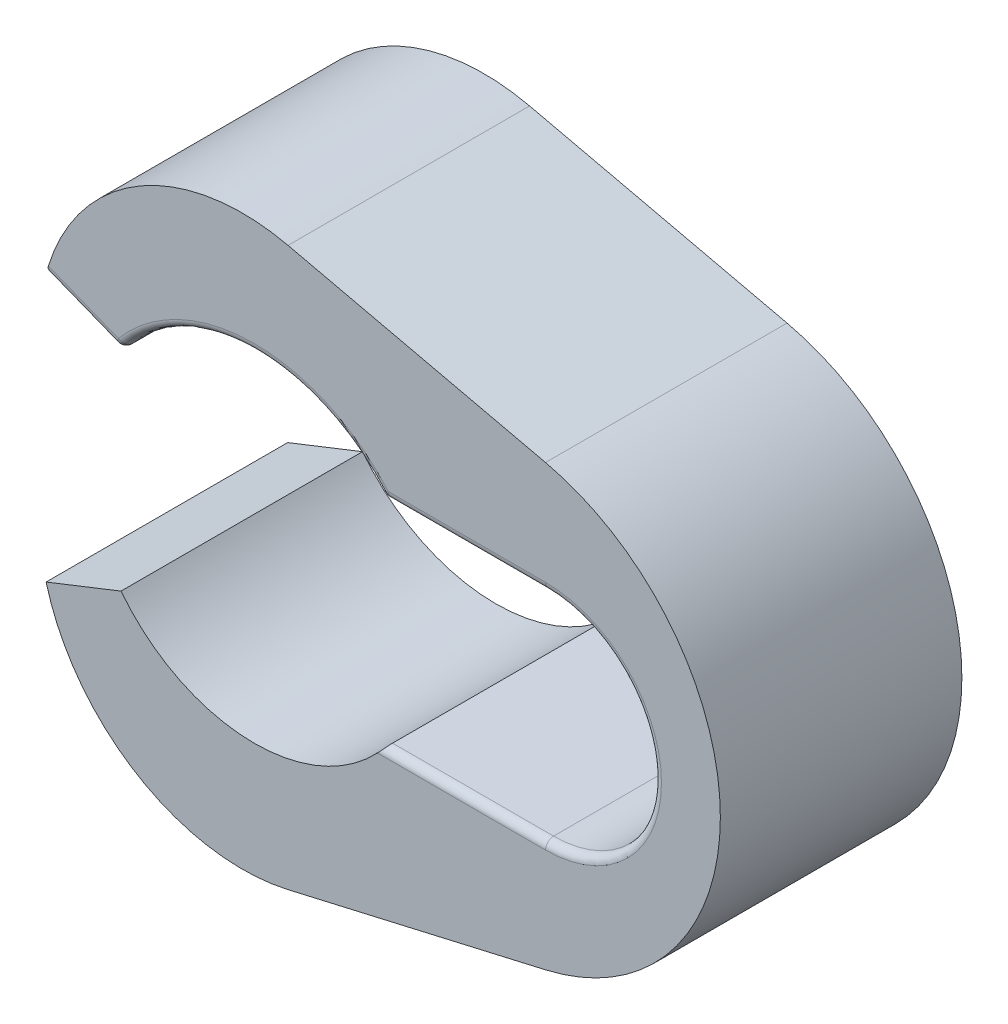
SolidWorks part; units mm, degrees
ref_plane "Plan de face" through (0, 0, 0) normal (0, 0, 1) x (1, 0, 0)
ref_plane "Plan de dessus" through (0, 0, 0) normal (0, 1, 0) x (1, 0, 0)
ref_plane "Plan de droite" through (0, 0, 0) normal (1, 0, 0) x (0, 0, -1)
sketch "Esquisse1" plane through (0, 0, 0) normal (0, 0, 1) x (1, 0, 0)
  line L0 (8.0846, 6.7) -> (18.0846, 6.7)
  line L2 (-8.2813, 6.4552) -> (-12.9318, 8.2919)
  line L3 (2.0932, 17.3259) -> (18.0846, 13.6428)
  line L4 (14.5282, 0) -> (-18.3892, 0) construction
  line L5 (8.0846, -6.7) -> (18.0846, -6.7)
  line L6 (2.0932, -17.3259) -> (18.0846, -13.6428)
  line L7 (-8.2813, -6.4552) -> (-12.9318, -8.2919)
  arc A0 (-8.2813, 6.4552) -> (8.0846, 6.7) centre (0, 0) cw
  arc A1 (18.0846, 6.7) -> (18.0846, -6.7) centre (18.0846, 0) cw
  arc A4 (18.0846, 13.6428) -> (18.0846, -13.6428) centre (14.9424, 0) cw
  arc A6 (-8.2813, -6.4552) -> (8.0846, -6.7) centre (0, 0) ccw
  arc A7 (2.0932, 17.3259) -> (-12.9318, 8.2919) centre (-0.7397, 5.0261) ccw
  arc A8 (2.0932, -17.3259) -> (-12.9318, -8.2919) centre (-0.7397, -5.0261) cw
  point P9 (2.0932, 17.3259)
  dimension "D3" = 6.7
  dimension "D5" = 5
  dimension "D7" = 14
  dimension "D6" = 10.5
  dimension "D4" = 10
extrude "Boss.-Extru.1" add sketch "Esquisse1" along normal blind 15
fillet "Congé1" radius 0.5 13 edges at (24.7846, 0, 15) (24.7846, 0, 0) (13.0846, 6.7, 15) (13.0846, 6.7, 0) (-10.6065, 7.3735, 15) (-10.6065, 7.3735, 0) (-8.2813, 6.4552, 7.5) (-0.157, 10.4988, 15) (8.0846, 6.7, 7.5) (-0.157, 10.4988, 0) (13.0846, -6.7, 15) (13.0846, -6.7, 0) (-12.9318, 8.2919, 7.5)
